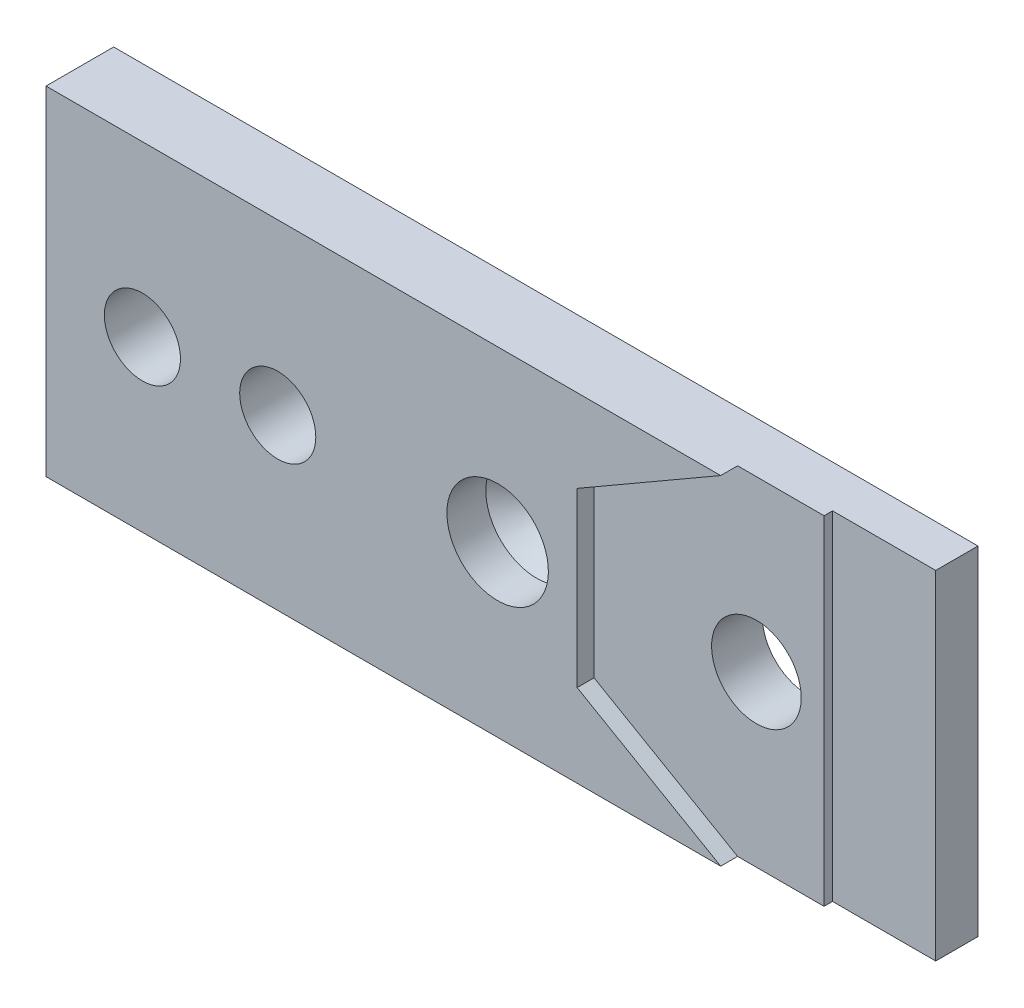
SolidWorks part; units mm, degrees
material "ABS"
ref_plane "Ebene vorne" through (0, 0, 0) normal (0, 0, 1) x (1, 0, 0)
ref_plane "Ebene oben" through (0, 0, 0) normal (0, 1, 0) x (1, 0, 0)
ref_plane "Ebene rechts" through (0, 0, 0) normal (1, 0, 0) x (0, 0, -1)
sketch "Skizze1" plane through (0, 0, 0) normal (0, 0, 1) x (1, 0, 0)
  line L0 (0, 0) -> (51.1, 0)
  line L1 (51.1, 0) -> (51.1, 2.5)
  line L2 (51.1, 2.5) -> (45, 2.5)
  line L3 (45, 2.5) -> (45, 3)
  line L4 (45, 3) -> (0, 3)
  line L5 (0, 3) -> (0, 0)
  line L6 (41, 3) -> (41, 0) construction
  line L7 (27, 3) -> (27, 0) construction
  line L8 (37, 3) -> (37, 0) construction
  line L9 (37.1, 0) -> (37.1, -6.2) construction
  line L10 (37.1, -6.2) -> (51.1, -6.2) construction
  line L11 (51.1, -6.2) -> (51.1, 0) construction
  line L12 (37.1, -6.2) -> (0, -6.2) construction
  line L13 (0, -6.2) -> (0, 0) construction
  line L14 (27, 0) -> (27, -6.2) construction
  line L15 (32, 3) -> (32, 6) construction
  circle A0 centre (27, 3) radius 1.65 construction
  circle A1 centre (41, 3) radius 2.65 construction
  circle A2 centre (14, 3) radius 1.65 construction
  circle A3 centre (6, 3) radius 1.65 construction
  dimension "D11" = 3.3
  dimension "D12" = 5.3
  dimension "D1" = 6.1
  dimension "D2" = 3
  dimension "D3" = 2.5
  dimension "D4" = 6
  dimension "D5" = 10.1
  dimension "D6" = 4
  dimension "D7" = 10
  dimension "D8" = 51.1
  dimension "D9" = 6.2
  dimension "D10" = 14
  dimension "D13" = 3
  dimension "D14" = 5
  dimension "D15" = 18
  dimension "D16" = 8
  dimension "D17" = 14
  dimension "D18" = 13
extrude "Aufsatz-Linear austragen1" add sketch "Skizze1" along normal blind 20
sketch "Skizze2" plane through (0, 0, 0) normal (0, -1, 0) x (1, 0, 0)
  line L0 (0, 10) -> (51.1, 10) construction
  line L1 (0, 20) -> (0, 0) construction
  line L2 (51.1, 20) -> (51.1, 0) construction
  circle A0 centre (26.7, 10) radius 1.65
  circle A1 centre (41, 10) radius 2.65
  circle A2 centre (13.7, 10) radius 2.25
  circle A3 centre (5.7, 10) radius 2.25
  circle A4 centre (26.7, 10) radius 3 construction
  point P15 (23.7, 10)
  dimension "D3" = 3.3
  dimension "D4" = 5.3
  dimension "D5" = 13
  dimension "D6" = 8
  dimension "D7" = 4.5
  dimension "D8" = 6
  dimension "D9" = 10
  dimension "D1" = 14.3
  dimension "D2" = 10.1
extrude "Schnitt-Linear austragen1" cut sketch "Skizze2" against normal up to surface (3 mm away) up to face at (22.5, 3, 10)
sketch "Skizze3" plane through (0, 3, 0) normal (0, 1, 0) x (1, 0, 0)
  line L0 (45, -20) -> (0, -20) construction
  line L1 (0, 0) -> (39.887, 0)
  line L2 (0, 0) -> (0, -20)
  line L3 (0, -20) -> (39.887, -20)
  line L4 (31.4, -4.9) -> (31.4, -15.1)
  line L5 (31.4, -15.1) -> (39.887, -20)
  line L6 (39.887, 0) -> (31.4, -4.9)
  line L7 (13.7, -10) -> (31.4, -10) construction
  line L9 (0, -10) -> (-2, -10)
  line L10 (0, -10) -> (0, -8)
  line L11 (0, -8) -> (-2, -8)
  line L12 (-2, -10) -> (-2, -8)
  circle A0 centre (26.7, -10) radius 1.65 construction
  circle A1 centre (13.7, -10) radius 2.25 construction
  circle A2 centre (5.7, -10) radius 2.25 construction
  circle A3 centre (13.7, -10) radius 2.25
  circle A4 centre (5.7, -10) radius 2.25
  circle A5 centre (26.7, -10) radius 1.65
  dimension "D1" = 4.7
  dimension "D4" = 2
  dimension "D2" = 10.2
  dimension "D3" = 120
extrude "Aufsatz-Linear austragen2" add sketch "Skizze3" along normal offset from surface (1 mm away) 4 up to face at (5.7, 0, 7.75)
sketch "Skizze4" plane through (0, 0, 10) normal (0, 0, 1) x (1, 0, 0)
  line L0 (26.7, 4) -> (26.7, 0) construction
  line L1 (0, 4) -> (39.887, 4) construction
  line L2 (0, 0) -> (51.1, 0) construction
  line L3 (23.7, 4) -> (23.7, 1.7)
  line L4 (23.7, 1.7) -> (25.2, 0.2)
  line L5 (25.2, 0.2) -> (26.7, 0.2)
  line L6 (28.35, 4) -> (25.05, 4) construction
  line L7 (28.35, 4) -> (25.05, 4) construction
  line L8 (26.7, 0.2) -> (26.7, 4)
  line L9 (26.7, 4) -> (23.7, 4)
  dimension "D1" = 45
  dimension "D2" = 3
  dimension "D3" = 1.5
  dimension "D4" = 0.2
revolve "Schnitt-Rotation3" cut sketch "Skizze4" angle 360 about L8
sketch "Skizze5" plane through (0, 4, 0) normal (0, 1, 0) x (1, 0, 0)
  line L1 (-2, -8) -> (0, -8)
  line L2 (-2, -8) -> (-2, -10)
  line L3 (-2, -10) -> (0, -10)
  line L4 (0, -8) -> (0, -10)
extrude "Schnitt-Linear austragen2" cut sketch "Skizze5" against normal up to surface (1 mm away) up to face at (-0.5, 3, 9.25)
move or copy body "Körper-Verschieben/Kopieren1" bodies to move or copy 107 copy no rotation origin (0, 1.5, 10) rotation axis (1, 0, 0) rotation angle 90
